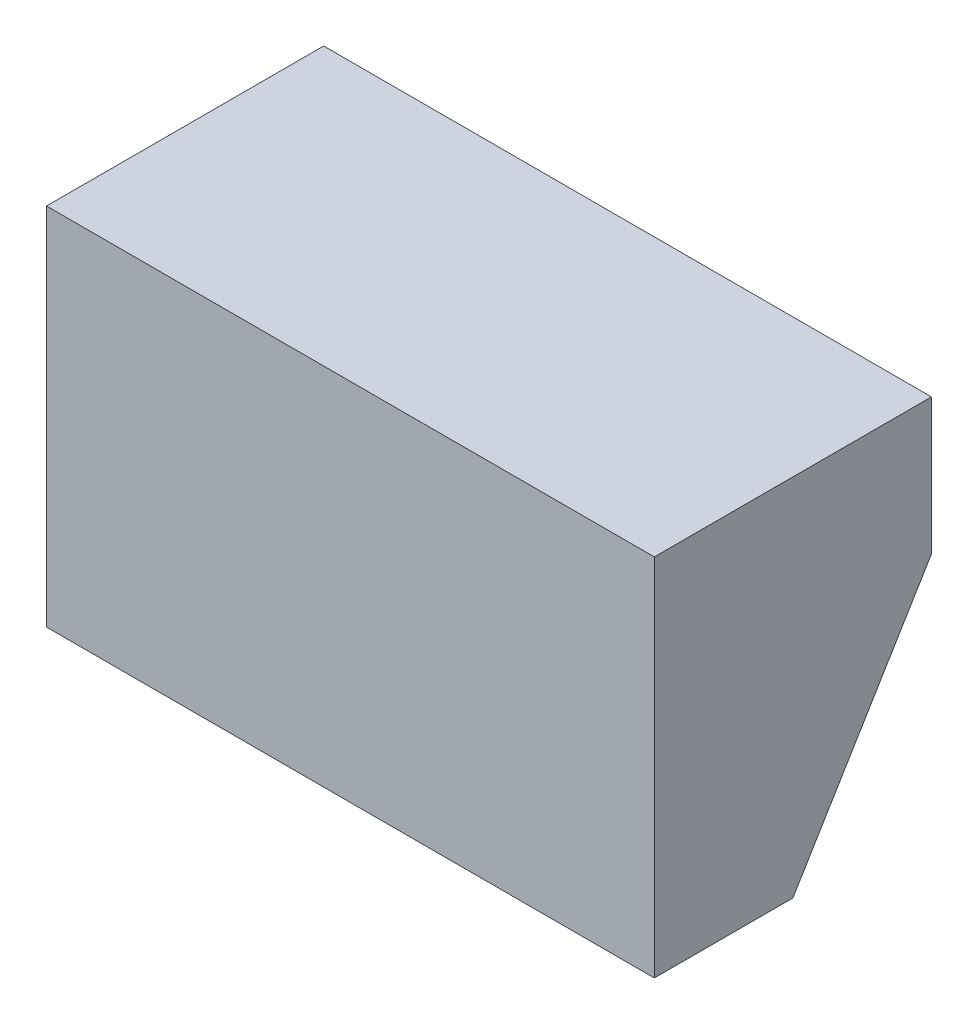
SolidWorks part; units mm, degrees
other "Defeature"
material "ABS PC"
ref_plane "前视基准面" through (0, 0, 0) normal (0, 0, 1) x (1, 0, 0)
ref_plane "上视基准面" through (0, 0, 0) normal (0, 1, 0) x (1, 0, 0)
ref_plane "右视基准面" through (0, 0, 0) normal (1, 0, 0) x (0, 0, -1)
sketch "Sketch1" plane through (0, 0, 0) normal (0, 0, 1) x (1, 0, 0)
  line L1 (-125, -75) -> (125, -75)
  line L2 (-125, -75) -> (-125, 75)
  line L3 (-125, 75) -> (125, 75)
  line L4 (125, -75) -> (125, 75)
  line L5 (-125, -75) -> (125, 75) construction
  line L6 (-125, 75) -> (125, -75) construction
  point P0 (0, 0)
  dimension "D1" = 250
  dimension "D2" = 150
extrude "Boss-Extrude1" add sketch "Sketch1" along normal blind 114
sketch "sketchCenterLine" plane through (0, 0, 114) normal (0, 0, 1) x (1, 0, 0)
  line L0 (0, 0) -> (-160.1488, 0) construction
  line L1 (-170, 12.5) -> (-115, 12.5)
  line L2 (-97.3223, 19.8223) -> (-69.467, 47.6777)
  line L3 (-51.7893, 55) -> (70, 55)
  line L4 (95, 30) -> (95, -30)
  line L5 (70, -55) -> (-51.7893, -55)
  line L6 (-69.467, -47.6777) -> (-97.3223, -19.8223)
  line L7 (-115, -12.5) -> (-170, -12.5)
  line L8 (-125, 75) -> (-125, -75) construction
  arc A0 (70, -55) -> (95, -30) centre (70, -30) ccw
  arc A1 (95, 30) -> (70, 55) centre (70, 30) ccw
  arc A2 (-115, 12.5) -> (-97.3223, 19.8223) centre (-115, 37.5) ccw
  arc A3 (-97.3223, -19.8223) -> (-115, -12.5) centre (-115, -37.5) ccw
  arc A4 (-51.7893, -55) -> (-69.467, -47.6777) centre (-51.7893, -30) cw
  arc A5 (-69.467, 47.6777) -> (-51.7893, 55) centre (-51.7893, 30) cw
  point P24 (-62.1447, -55)
  point P27 (-62.1447, 55)
  dimension "D1" = 25
  dimension "D2" = 25
  dimension "D8" = 10
  dimension "D3" = 95
  dimension "D4" = 110
  dimension "D5" = 25
  dimension "D6" = 45
  dimension "D7" = 45
sketch3d "3DSketch1"
  line L0 (125, -75, 114) -> (125, -75, 0) construction
  line L1 (125, -75, 0) -> (125, 75, 0) construction
  line L2 (-125, -75, 0) -> (125, -75, 0) construction
  point P0 (125, -75, 57)
  point P1 (125, 19.0618, 0)
  point P4 (42.2925, -75, 0)
ref_plane "Plane1" through (27.9069, -24.5383, -40.4932) normal (-0.5078, 0.4465, 0.7368) x (0.8615, 0.2632, 0.4343)
sketch "Sketch4" plane through (27.9069, -24.5383, -40.4932) normal (-0.5078, 0.4465, 0.7368) x (0.8615, 0.2632, 0.4343)
  line L1 (-16.3307, -143.8321) -> (142.4953, -143.8321)
  line L2 (-16.3307, -143.8321) -> (-16.3307, 25.2667)
  line L3 (-16.3307, 25.2667) -> (142.4953, 25.2667)
  line L4 (142.4953, -143.8321) -> (142.4953, 25.2667)
extrude "Cut-Extrude1" cut sketch "Sketch4" against normal blind 114
sketch "Sketch5" plane through (0, 0, 0) normal (0, 0, -1) x (-1, 0, 0)
  circle A0 centre (25.5219, 0) radius 21.2567
extrude "Cut-Extrude2" cut sketch "Sketch5" against normal blind 54
